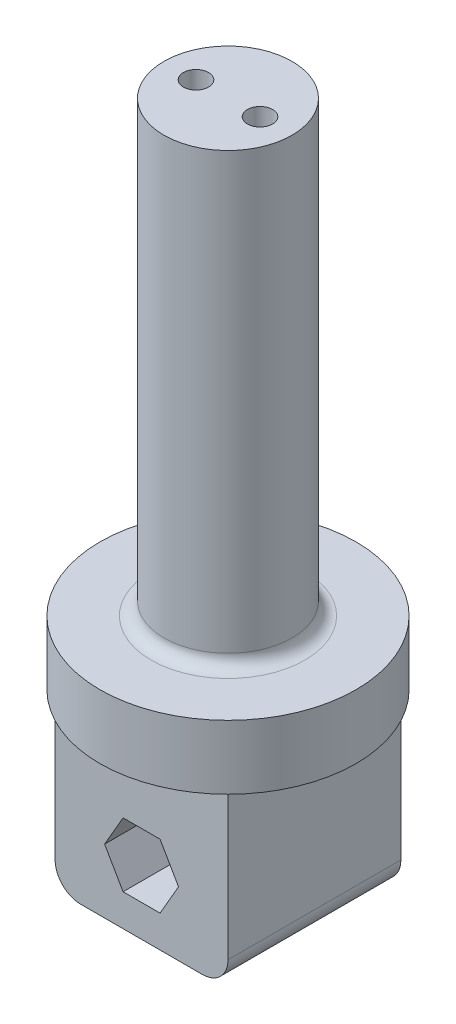
SolidWorks part; units mm, degrees
ref_plane "Front Plane" through (0, 0, 0) normal (0, 0, 1) x (1, 0, 0)
ref_plane "Top Plane" through (0, 0, 0) normal (0, 1, 0) x (1, 0, 0)
ref_plane "Right Plane" through (0, 0, 0) normal (1, 0, 0) x (0, 0, -1)
sketch "Sketch3" plane through (0, 0, 0) normal (0, 1, 0) x (1, 0, 0)
  line L0 (0, 0) -> (17.145, 0)
  line L1 (-27.94, 0) -> (27.94, 0) construction
  line L2 (17.145, 0) -> (17.145, 17.145)
  line L3 (17.145, 17.145) -> (0, 17.145)
  line L4 (0, -27.94) -> (0, 27.94) construction
  line L5 (0, 17.145) -> (-17.145, 17.145)
  line L6 (-17.145, 17.145) -> (-17.145, 0)
  line L7 (-17.145, 0) -> (-17.145, -17.145)
  line L8 (-17.145, -17.145) -> (0, -17.145)
  line L9 (0, -17.145) -> (17.145, -17.145)
  line L10 (17.145, -17.145) -> (17.145, 0)
extrude "Boss-Extrude1" add sketch "Sketch3" along normal blind 34.317 contours L2 L3 L5 L6 L7 L8 L9 L10
sketch "Sketch4" plane through (0, 34.317, 0) normal (0, 1, 0) x (1, 0, 0)
  circle A0 centre (0, 0) radius 25.4
  dimension "D1" = 50.8
extrude "Boss-Extrude2" add sketch "Sketch4" along normal blind 12.7 contours A0
sketch "Sketch6" plane through (0, 47.017, 0) normal (0, 1, 0) x (1, 0, 0)
  circle A0 centre (0, 0) radius 12.7
  dimension "D1" = 25.4
extrude "Boss-Extrude3" add sketch "Sketch6" along normal blind 88.9 contours A0
sketch "Sketch7" plane through (0, 0, 17.145) normal (0, 0, 1) x (1, 0, 0)
  line L0 (0, 0) -> (0, 12.7)
  line L1 (0, -27.94) -> (0, 27.94) construction
  line L3 (7.3323, 12.7) -> (3.6662, 19.05)
  line L4 (3.6662, 19.05) -> (-3.6662, 19.05)
  line L5 (-3.6662, 19.05) -> (-7.3323, 12.7)
  line L6 (-7.3323, 12.7) -> (-3.6662, 6.35)
  line L7 (-3.6662, 6.35) -> (3.6662, 6.35)
  line L8 (3.6662, 6.35) -> (7.3323, 12.7)
  circle A0 centre (0, 12.7) radius 6.35 construction
  point P5 (-5.4993, 15.875)
  dimension "D1" = 12.7
  dimension "D2" = 12.7
extrude "Cut-Extrude1" cut sketch "Sketch7" against normal through all
fillet "Fillet1" radius 5.08 2 edges at (17.145, 0, 0) (-17.145, 0, 0)
sketch "Sketch10" plane through (0, 135.917, 0) normal (0, 1, 0) x (1, 0, 0)
  line L0 (0, 0) -> (6.35, 0)
  line L1 (-27.94, 0) -> (27.94, 0) construction
  line L2 (0, 0) -> (-6.35, 0)
  point P5 (0, 0)
  dimension "D1" = 12.7
fillet "Fillet2" radius 2.54 1 edges at (0, 47.017, 12.7)
hole_wizard "M6x1.0 Tapped Hole1" positions "Sketch11" profile "Sketch13" tap size "M6x1.0" standard "ANSI Metric"
sketch "Sketch11" plane through (0, 135.917, 0) normal (0, 1, 0) x (1, 0, 0)
  point P0 (6.35, 0)
  point P3 (-6.35, 0)
sketch "Sketch13" plane through (6.35, 135.917, 0) normal (1, 0, 0) x (0, 0, 1)
  line L0 (0, 0) -> (0, 39.6022)
  line L1 (0, 39.6022) -> (2.5, 38.1)
  line L2 (2.5, 38.1) -> (2.5, 0)
  line L5 (2.5, 0) -> (0, 0)
  line L10 (0, 39.6022) -> (-2.5, 38.1) construction
  line L11 (0, -6.35) -> (0, 107.95) construction
  dimension "Tap Drill Dia." = 5
  dimension "Tap Drill Depth" = 38.1
  dimension "Drill Angle" = 118
equation "\"Trochanter-Iliac-diff\"= 4in"
equation "\"rodsquareside\"= 1.35in"
equation "\"axisdiff\"= 2.6489381in"
equation "\"hexsize\"= 0.5in"
equation "\"hexcentertobottom\"= 0.5in"
equation "\"D1@Sketch3\"=\"rodsquareside\""
equation "\"collarheight\"= 0.5in"
equation "\"D1@Boss-Extrude1\"=\"Trochanter-Iliac-diff\"-\"collarheight\"-\"axisdiff\"+\"hexcentertobottom\""
equation "\"rodthickness\"= 2in"
equation "\"plateheight\"= 3.5in"
equation "\"lidscrewholedepth\"= 0.5in"
equation "\"D1@Sketch4\"=\"rodthickness\""
equation "\"D1@Boss-Extrude2\"=\"collarheight\""
equation "\"rodaxlethickness\"= 1in"
equation "\"D1@Sketch6\"=\"rodaxlethickness\""
equation "\"D1@Boss-Extrude3\"=\"plateheight\""
equation "\"D1@Sketch7\"=\"hexcentertobottom\""
equation "\"D2@Sketch7\"=\"hexsize\""
equation "\"rodsquarefiletradius\"= 0.2in"
equation "\"D1@Fillet1\"=\"rodsquarefiletradius\""
equation "\"lidscrewholediff\"= 0.5in"
equation "\"D1@Sketch10\"=\"lidscrewholediff\""
equation "\"filetradius\"= 0.1in"
equation "\"D1@Fillet2\"=\"filetradius\""
